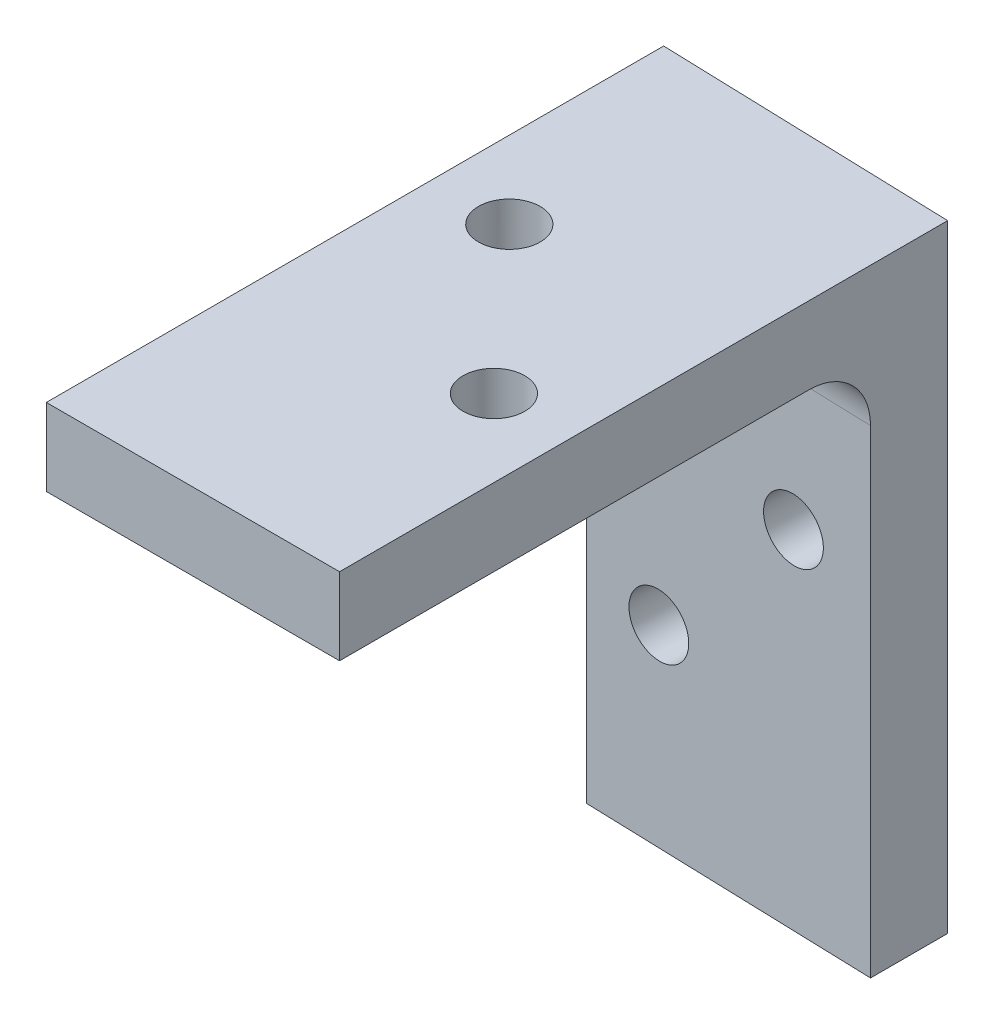
SolidWorks part; units mm, degrees
ref_plane "Front Plane" through (0, 0, 0) normal (0, 0, 1) x (1, 0, 0)
ref_plane "Top Plane" through (0, 0, 0) normal (0, 1, 0) x (1, 0, 0)
ref_plane "Right Plane" through (0, 0, 0) normal (1, 0, 0) x (0, 0, -1)
sketch "Sketch1" plane through (0, 0, 0) normal (0, 1, 0) x (1, 0, 0)
  line L1 (-9.5, -20) -> (9.5, -20)
  line L2 (-9.5, -20) -> (-9.5, 20)
  line L3 (-9.5, 20) -> (9.5, 20)
  line L4 (9.5, -20) -> (9.5, 20)
  line L5 (-9.5, -20) -> (9.5, 20) construction
  line L6 (-9.5, 20) -> (9.5, -20) construction
  point P0 (0, 0)
  dimension "D1" = 19
  dimension "D2" = 40
extrude "Boss-Extrude1" add sketch "Sketch1" along normal blind 5
sketch "Sketch2" plane through (0, 5, 0) normal (0, 1, 0) x (1, 0, 0)
  line L0 (-9.5, 20) -> (9.5, 20)
  line L1 (9.5, 20) -> (9.5, 19.4029)
  line L2 (9.5, -20) -> (9.5, 20) construction
  line L3 (9.5, 19.4029) -> (-9.5, 20)
  dimension "D1" = 1.8
extrude "Cut-Extrude1" cut sketch "Sketch2" against normal through all
sketch "Sketch4" plane through (0, 0, 0) normal (0, -1, 0) x (1, 0, 0)
  line L0 (9.5, -19.4029) -> (-9.5, -20)
  line L1 (-9.5, -20) -> (-9.5, -15)
  line L2 (-9.5, -20) -> (-9.5, 20) construction
  line L3 (-9.5, -15) -> (9.5, -14.4029)
  line L4 (9.5, 20) -> (9.5, -19.4029) construction
  line L5 (9.5, -14.4029) -> (9.5, -19.4029)
  dimension "D1" = 5
extrude "Boss-Extrude2" add sketch "Sketch4" along normal blind 35
sketch "Sketch5" plane through (0, 5, 0) normal (0, 1, 0) x (1, 0, 0)
  line L0 (-9.5, 20) -> (-9.5, -20) construction
  line L1 (9.5, -20) -> (9.5, 19.4029) construction
  line L2 (-9.5, -20) -> (9.5, -20) construction
  circle A0 centre (-4.5, 5) radius 2
  circle A1 centre (4.5, -5) radius 2
  dimension "D1" = 4
  dimension "D2" = 4
  dimension "D3" = 5
  dimension "D4" = 5
  dimension "D5" = 10
  dimension "D6" = 15
extrude "Cut-Extrude2" cut sketch "Sketch5" against normal through all
sketch "Sketch6" plane through (0.6185, 0, -19.682) normal (0.0314, 0, -0.9995) x (-0.9995, 0, -0.0314)
  line L1 (10.1235, 5) -> (10.1235, -35) construction
  line L2 (-8.8859, -35) -> (-8.8859, 5) construction
  line L3 (10.1235, -35) -> (-8.8859, -35) construction
  circle A0 centre (-3.8859, -12.5) radius 2
  circle A1 centre (5.1235, -22.5) radius 2
  dimension "D1" = 4
  dimension "D2" = 4
  dimension "D3" = 5
  dimension "D4" = 5
  dimension "D6" = 12.5
  dimension "D5" = 10
extrude "Cut-Extrude3" cut sketch "Sketch6" against normal through all
fillet "Fillet1" radius 4 1 edges at (0, 0, -14.7015)
